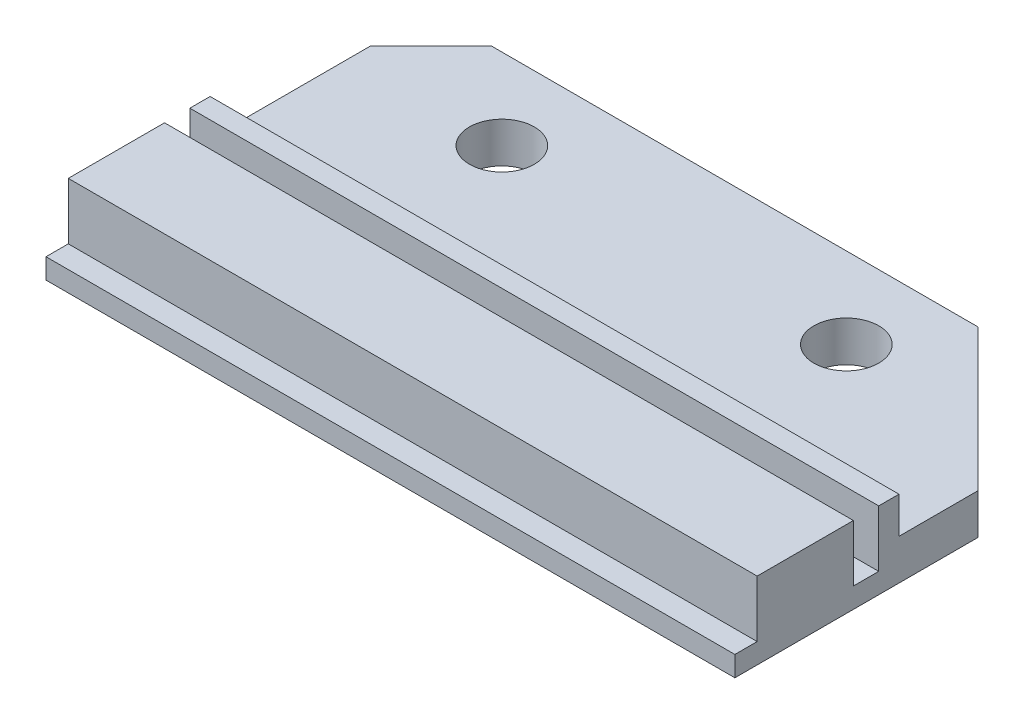
SolidWorks part; units mm, degrees
ref_plane "前视基准面" through (0, 0, 0) normal (0, 0, 1) x (1, 0, 0)
ref_plane "上视基准面" through (0, 0, 0) normal (0, 1, 0) x (1, 0, 0)
ref_plane "右视基准面" through (0, 0, 0) normal (1, 0, 0) x (0, 0, -1)
other "Configuration Table"
sketch "草图1" plane through (0, 0, 0) normal (0, 1, 0) x (1, 0, 0)
  line L0 (0, 0) -> (17, 0) construction
  line L1 (8.5, 4) -> (8.5, 0) construction
  line L2 (-7.5, 4) -> (24.5, 4)
  line L3 (-7.5, 4) -> (-7.5, -15)
  line L4 (-7.5, -15) -> (24.5, -15)
  line L5 (24.5, 4) -> (24.5, -15)
  circle A0 centre (0, 0) radius 1.6
  circle A1 centre (17, 0) radius 1.6
  dimension "D1" = 3.2
  dimension "D2" = 17
  dimension "D3" = 4
  dimension "D4" = 32
  dimension "D5" = 15
extrude "凸台-拉伸1" add sketch "草图1" along normal blind 1
sketch "草图3" plane through (0, 1, 0) normal (0, 1, 0) x (1, 0, 0)
  line L0 (-7.5, 4) -> (-7.5, -15) construction
  line L1 (-7.5, -9.15) -> (24.5, -9.15)
  line L2 (-7.5, -9.15) -> (-7.5, -13.9)
  line L3 (-7.5, -13.9) -> (24.5, -13.9)
  line L4 (24.5, -9.15) -> (24.5, -13.9)
  line L5 (24.5, -15) -> (24.5, 4) construction
  line L6 (-7.5, -15) -> (24.5, -15) construction
  dimension "D1" = 1.1
  dimension "D2" = 4.75
extrude "凸台-拉伸2" add sketch "草图3" along normal blind 2.8
sketch "草图4" plane through (0, 1, 0) normal (0, 1, 0) x (1, 0, 0)
  line L0 (-7.5, 4) -> (-7.5, -9.15) construction
  line L1 (-7.5, -6.9) -> (24.5, -6.9)
  line L2 (-7.5, -6.9) -> (-7.5, -7.9)
  line L3 (-7.5, -7.9) -> (24.5, -7.9)
  line L4 (24.5, -6.9) -> (24.5, -7.9)
  line L5 (24.5, -9.15) -> (24.5, 4) construction
  line L6 (24.5, -9.15) -> (-7.5, -9.15) construction
  dimension "D1" = 1
  dimension "D2" = 1.25
extrude "凸台-拉伸3" add sketch "草图4" along normal up to surface (2.8 mm away) up to face at (8.5, 3.8, 11.525)
sketch "草图5" plane through (24.5, 0, 0) normal (1, 0, 0) x (0, 0, -1)
  line L12 (-15, 0) -> (4, 0)
  line L13 (4, 0) -> (4, 1)
  line L14 (4, 1) -> (-6.9, 1)
  line L15 (-6.9, 1) -> (-6.9, 3.8)
  line L16 (-6.9, 3.8) -> (-7.9, 3.8)
  line L17 (-7.9, 3.8) -> (-7.9, 1)
  line L18 (-7.9, 1) -> (-9.15, 1)
  line L19 (-9.15, 1) -> (-9.15, 3.8)
  line L20 (-9.15, 3.8) -> (-13.9, 3.8)
  line L21 (-13.9, 3.8) -> (-13.9, 1)
  line L22 (-13.9, 1) -> (-15, 1)
  line L23 (-15, 1) -> (-15, 0)
  line L24 (-15, 0) -> (4, 0)
  line L25 (4, 0) -> (4, 1)
  line L26 (4, 1) -> (-6.9, 1)
  line L27 (-6.9, 1) -> (-6.9, 3.8)
  line L28 (-6.9, 3.8) -> (-7.9, 3.8)
  line L29 (-7.9, 3.8) -> (-7.9, 1)
  line L30 (-7.9, 1) -> (-9.15, 1)
  line L31 (-9.15, 1) -> (-9.15, 3.8)
  line L32 (-9.15, 3.8) -> (-13.9, 3.8)
  line L33 (-13.9, 3.8) -> (-13.9, 1)
  line L34 (-13.9, 1) -> (-15, 1)
  line L35 (-15, 1) -> (-15, 0)
  dimension "D1" = 0
extrude "凸台-拉伸4" add sketch "草图5" along normal blind 2
sketch "草图6" plane through (-7.5, 0, 0) normal (-1, 0, 0) x (0, 0, 1)
  line L12 (-4, 0) -> (15, 0)
  line L13 (15, 0) -> (15, 1)
  line L14 (15, 1) -> (13.9, 1)
  line L15 (13.9, 1) -> (13.9, 3.8)
  line L16 (13.9, 3.8) -> (9.15, 3.8)
  line L17 (9.15, 3.8) -> (9.15, 1)
  line L18 (9.15, 1) -> (7.9, 1)
  line L19 (7.9, 1) -> (7.9, 3.8)
  line L20 (7.9, 3.8) -> (6.9, 3.8)
  line L21 (6.9, 3.8) -> (6.9, 1)
  line L22 (6.9, 1) -> (-4, 1)
  line L23 (-4, 1) -> (-4, 0)
  line L24 (-4, 0) -> (15, 0)
  line L25 (15, 0) -> (15, 1)
  line L26 (15, 1) -> (13.9, 1)
  line L27 (13.9, 1) -> (13.9, 3.8)
  line L28 (13.9, 3.8) -> (9.15, 3.8)
  line L29 (9.15, 3.8) -> (9.15, 1)
  line L30 (9.15, 1) -> (7.9, 1)
  line L31 (7.9, 1) -> (7.9, 3.8)
  line L32 (7.9, 3.8) -> (6.9, 3.8)
  line L33 (6.9, 3.8) -> (6.9, 1)
  line L34 (6.9, 1) -> (-4, 1)
  line L35 (-4, 1) -> (-4, 0)
  dimension "D1" = 0
extrude "凸台-拉伸5" add sketch "草图6" along normal blind 7
chamfer "倒角1" distance 7 angle 45 2 edges at (26.5, 0.5, -4) (-14.5, 0.5, -4)
sketch "草图7" plane through (0, 1, 0) normal (0, 1, 0) x (1, 0, 0)
  line L6 (26.5, -6.9) -> (26.5, -3)
  line L7 (26.5, -3) -> (19.5, 4)
  line L8 (19.5, 4) -> (-7.5, 4)
  line L9 (-7.5, 4) -> (-14.5, -3)
  line L10 (-14.5, -3) -> (-14.5, -6.9)
  line L11 (-14.5, -6.9) -> (26.5, -6.9)
  line L12 (26.5, -6.9) -> (26.5, -3)
  line L13 (26.5, -3) -> (19.5, 4)
  line L14 (19.5, 4) -> (-7.5, 4)
  line L15 (-7.5, 4) -> (-14.5, -3)
  line L16 (-14.5, -3) -> (-14.5, -6.9)
  line L17 (-14.5, -6.9) -> (26.5, -6.9)
  circle A0 centre (17, 0) radius 1.6 construction
  circle A1 centre (0, 0) radius 1.6 construction
  circle A2 centre (17, 0) radius 1.6
  circle A3 centre (0, 0) radius 1.6
  dimension "D1" = 0
extrude "凸台-拉伸6" add sketch "草图7" along normal blind 1
sketch "草图8" plane through (0, 3.8, 0) normal (0, 1, 0) x (1, 0, 0)
  line L0 (-14.5, -15) -> (26.5, -15) construction
  line L1 (-14.5, 1) -> (-10.5, 1)
  line L2 (-14.5, 1) -> (-14.5, -15)
  line L3 (-14.5, -15) -> (-10.5, -15)
  line L4 (-10.5, 1) -> (-10.5, -15)
  line L5 (-14.5, 1) -> (-10.5, -15) construction
  line L6 (-14.5, -15) -> (-10.5, 1) construction
  line L7 (26.5, -6.9) -> (26.5, -7.9) construction
  line L8 (-7.5, 4) -> (-14.5, -3) construction
  point P4 (-12.5, -7)
  dimension "D1" = 37
extrude "切除-拉伸1" cut sketch "草图8" against normal through all
sketch "草图9" plane through (0, 2, 0) normal (0, 1, 0) x (1, 0, 0)
  line L1 (-10.5, -6.9) -> (16.5, -6.9)
  line L2 (-10.5, -6.9) -> (-10.5, -5.4)
  line L3 (-10.5, -5.4) -> (16.5, -5.4)
  line L4 (16.5, -6.9) -> (16.5, -5.4)
  line L5 (-10.5, -6.9) -> (16.5, -5.4) construction
  line L6 (-10.5, -5.4) -> (16.5, -6.9) construction
  point P4 (3, -6.15)
  dimension "D1" = 1.5
  dimension "D2" = 27
extrude "切除-拉伸2" cut sketch "草图9" against normal offset from surface (1 mm away) 1 up to face at (7.3333, 0, 4)
sketch "草图10" plane through (0, 0, 0) normal (0, -1, 0) x (1, 0, 0)
  line L0 (19.5, -4) -> (-7.5, -4) construction
  line L1 (-10.5, 15) -> (-7.5, 15)
  line L2 (-10.5, 15) -> (-10.5, -4)
  line L3 (-10.5, -4) -> (-7.5, -4)
  line L4 (-7.5, 15) -> (-7.5, -4)
  line L5 (-10.5, 15) -> (-7.5, -4) construction
  line L6 (-10.5, -4) -> (-7.5, 15) construction
  point P4 (-9, 5.5)
  dimension "D1" = 3
extrude "切除-拉伸3" cut sketch "草图10" against normal through all
chamfer "倒角2" distance 3 angle 45 1 edges at (-7.5, 1, -4)
sketch "草图11" plane through (0, 0, 0) normal (0, -1, 0) x (1, 0, 0)
  line L0 (-7.5, -1) -> (-4.5, -4) construction
  line L1 (-7.5, 15) -> (-6, 15)
  line L2 (-7.5, 15) -> (-7.5, -2.5)
  line L3 (-7.5, -2.5) -> (-6, -2.5)
  line L4 (-6, 15) -> (-6, -2.5)
  dimension "D1" = 1.5
